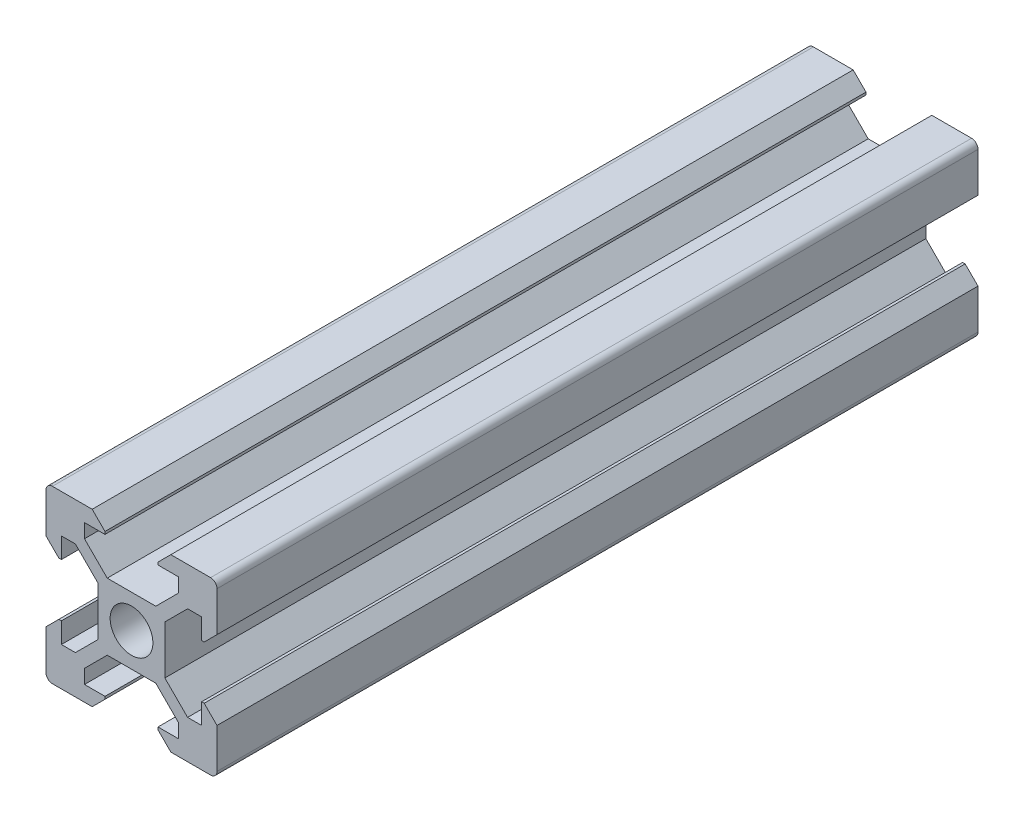
SolidWorks part; units mm, degrees
ref_plane "Alzado" through (0, 0, 0) normal (0, 0, 1) x (1, 0, 0)
ref_plane "Planta" through (0, 0, 0) normal (0, 1, 0) x (1, 0, 0)
ref_plane "Vista lateral" through (0, 0, 0) normal (1, 0, 0) x (0, 0, -1)
sketch "Croquis1" plane through (0, 0, 0) normal (0, 0, 1) x (1, 0, 0)
  line L0 (-4.6, 10) -> (-3.1, 8.5)
  line L3 (-4.6, 10) -> (-9.25, 10)
  line L5 (-3.1, 8.5) -> (-3.1, 8.2)
  line L6 (-3.1, 8.2) -> (-5.5, 8.2)
  line L7 (-5.5, 8.2) -> (-5.5, 6.5607)
  line L8 (-5.5, 6.5607) -> (-2.84, 3.9007)
  line L9 (-2.84, 3.9007) -> (0, 3.9007)
  line L10 (0, 0) -> (-15.3499, 15.3499) construction
  line L11 (-3.9007, 2.84) -> (-3.9007, 0)
  line L12 (-6.5607, 5.5) -> (-3.9007, 2.84)
  line L13 (-8.2, 5.5) -> (-6.5607, 5.5)
  line L14 (-8.2, 3.1) -> (-8.2, 5.5)
  line L15 (-8.5, 3.1) -> (-8.2, 3.1)
  line L16 (-10, 4.6) -> (-10, 9.25)
  line L17 (-10, 4.6) -> (-8.5, 3.1)
  line L18 (10, 4.6) -> (8.5, 3.1)
  line L19 (10, 4.6) -> (10, 9.25)
  line L20 (8.5, 3.1) -> (8.2, 3.1)
  line L21 (8.2, 3.1) -> (8.2, 5.5)
  line L22 (8.2, 5.5) -> (6.5607, 5.5)
  line L23 (6.5607, 5.5) -> (3.9007, 2.84)
  line L24 (3.9007, 2.84) -> (3.9007, 0)
  line L25 (5.5, 6.5607) -> (2.84, 3.9007)
  line L26 (5.5, 8.2) -> (5.5, 6.5607)
  line L27 (3.1, 8.2) -> (5.5, 8.2)
  line L28 (3.1, 8.5) -> (3.1, 8.2)
  line L29 (4.6, 10) -> (9.25, 10)
  line L30 (4.6, 10) -> (3.1, 8.5)
  line L31 (2.84, 3.9007) -> (0, 3.9007)
  line L32 (4.6, -10) -> (3.1, -8.5)
  line L33 (4.6, -10) -> (9.25, -10)
  line L34 (3.1, -8.5) -> (3.1, -8.2)
  line L35 (3.1, -8.2) -> (5.5, -8.2)
  line L36 (5.5, -8.2) -> (5.5, -6.5607)
  line L37 (5.5, -6.5607) -> (2.84, -3.9007)
  line L38 (2.84, -3.9007) -> (0, -3.9007)
  line L39 (6.5607, -5.5) -> (3.9007, -2.84)
  line L40 (8.2, -5.5) -> (6.5607, -5.5)
  line L41 (8.2, -3.1) -> (8.2, -5.5)
  line L42 (8.5, -3.1) -> (8.2, -3.1)
  line L43 (10, -4.6) -> (10, -9.25)
  line L44 (10, -4.6) -> (8.5, -3.1)
  line L45 (3.9007, -2.84) -> (3.9007, 0)
  line L46 (-10, -4.6) -> (-8.5, -3.1)
  line L47 (-10, -4.6) -> (-10, -9.25)
  line L48 (-8.5, -3.1) -> (-8.2, -3.1)
  line L49 (-8.2, -3.1) -> (-8.2, -5.5)
  line L50 (-8.2, -5.5) -> (-6.5607, -5.5)
  line L51 (-6.5607, -5.5) -> (-3.9007, -2.84)
  line L52 (-3.9007, -2.84) -> (-3.9007, 0)
  line L53 (-5.5, -6.5607) -> (-2.84, -3.9007)
  line L54 (-5.5, -8.2) -> (-5.5, -6.5607)
  line L55 (-3.1, -8.2) -> (-5.5, -8.2)
  line L56 (-3.1, -8.5) -> (-3.1, -8.2)
  line L57 (-4.6, -10) -> (-9.25, -10)
  line L58 (-4.6, -10) -> (-3.1, -8.5)
  line L59 (-2.84, -3.9007) -> (0, -3.9007)
  circle A0 centre (0, 0) radius 2.5
  arc A1 (-9.25, 10) -> (-10, 9.25) centre (-9.25, 9.25) ccw
  arc A2 (10, 9.25) -> (9.25, 10) centre (9.25, 9.25) ccw
  arc A3 (9.25, -10) -> (10, -9.25) centre (9.25, -9.25) ccw
  arc A4 (-10, -9.25) -> (-9.25, -10) centre (-9.25, -9.25) ccw
  point P18 (-10, 10)
  point P37 (10, 10)
  point P55 (10, -10)
  point P73 (-10, -10)
  point P79 (0, 0)
  dimension "D1" = 5
  dimension "D5" = 0.75
  dimension "D2" = 10
  dimension "D3" = 10
  dimension "D4" = 4.6
  dimension "D6" = 5.5
  dimension "D7" = 135
  dimension "D8" = 0.75
  dimension "D9" = 225
  dimension "D10" = 2.84
  dimension "D11" = 1.8
  dimension "D12" = 3.1
  dimension "D13" = 4
extrude "Saliente-Extruir1" add sketch "Croquis1" along normal blind 89
